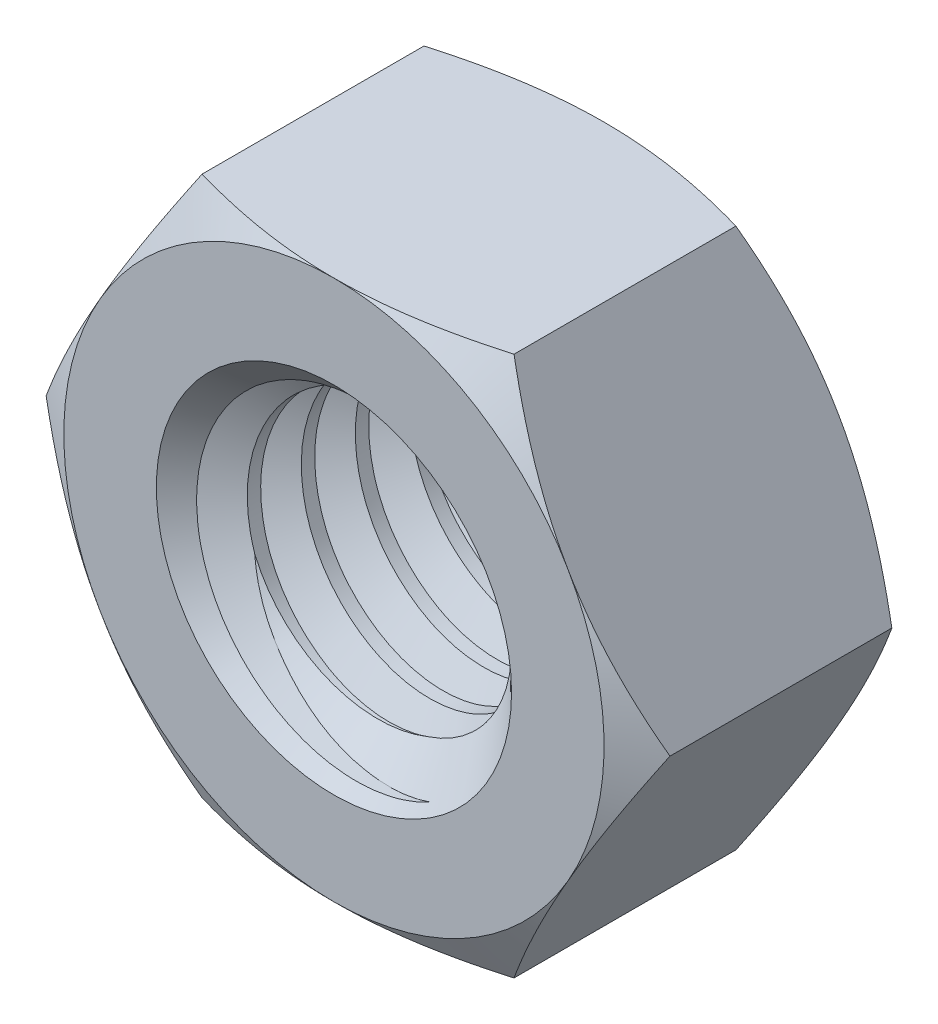
SolidWorks part; units mm, degrees
ref_plane "Front Plane" through (0, 0, 0) normal (0, 0, 1) x (1, 0, 0)
ref_plane "Top  Plane" through (0, 0, 0) normal (0, 1, 0) x (1, 0, 0)
ref_plane "Right  Plane" through (0, 0, 0) normal (1, 0, 0) x (0, 0, -1)
sketch "Çizim1" plane through (0, 0, 0) normal (0, 0, 1) x (1, 0, 0)
  line L1 (4.6188, 0) -> (2.3094, 4)
  line L2 (2.3094, 4) -> (-2.3094, 4)
  line L3 (-2.3094, 4) -> (-4.6188, 0)
  line L4 (-4.6188, 0) -> (-2.3094, -4)
  line L5 (-2.3094, -4) -> (2.3094, -4)
  line L6 (2.3094, -4) -> (4.6188, 0)
  circle A0 centre (0, 0) radius 4 construction
  dimension "D1" = 8
extrude "Boss-Extrude1" add sketch "Çizim1" along normal blind 4
sketch "Çizim2" plane through (0, 0, 4) normal (0, 0, 1) x (1, 0, 0)
  circle A0 centre (0, 0) radius 4
extrude "Cut-Extrude1" cut sketch "Çizim2" against normal blind 4 draft 60 flip side to cut
sketch "Çizim3" plane through (0, 0, 0) normal (0, 0, -1) x (-1, 0, 0)
  circle A0 centre (0, 0) radius 4
extrude "Cut-Extrude2" cut sketch "Çizim3" against normal blind 4 draft 60 flip side to cut
sketch "Çizim4" plane through (0, 0, 4) normal (0, 0, 1) x (1, 0, 0)
  circle A0 centre (0, 0) radius 1.98
  dimension "D1" = 3.96
extrude "Cut-Extrude3" cut sketch "Çizim4" against normal blind 4
chamfer "Chamfer1" distance 0.65 angle 45 2 edges at (1.98, 0, 0) (1.98, 0, 4)
sketch "Çizim5" plane through (0, 0, 0) normal (0, 0, -1) x (-1, 0, 0)
  circle A0 centre (0, 0) radius 1.98
curve "Helis/Spiral1" pitch 0.8 height 5 turns 6.25
ref_plane "Plane1" through (0, 1.98, 5) normal (-0.9979, 0, 0.0642) x (0.0642, 0, 0.9979)
sketch "Çizim6" plane through (0, 1.98, 5) normal (-0.9979, 0, 0.0642) x (0.0642, 0, 0.9979)
  line L1 (0, 0.52) -> (-0.3833, -0.1439)
  line L3 (0.3833, -0.1439) -> (0, 0.52)
  line L4 (0.3833, -0.1439) -> (-0.3833, -0.1439)
  line L5 (0, -0.26) -> (0.4503, -0.26) [skipped]
  circle A0 centre (0, 0) radius 0.26 construction
  dimension "D1" = 0.52
sweep "Cut-Swept1" cut profiles "Çizim6" path "Helis/Spiral1"
